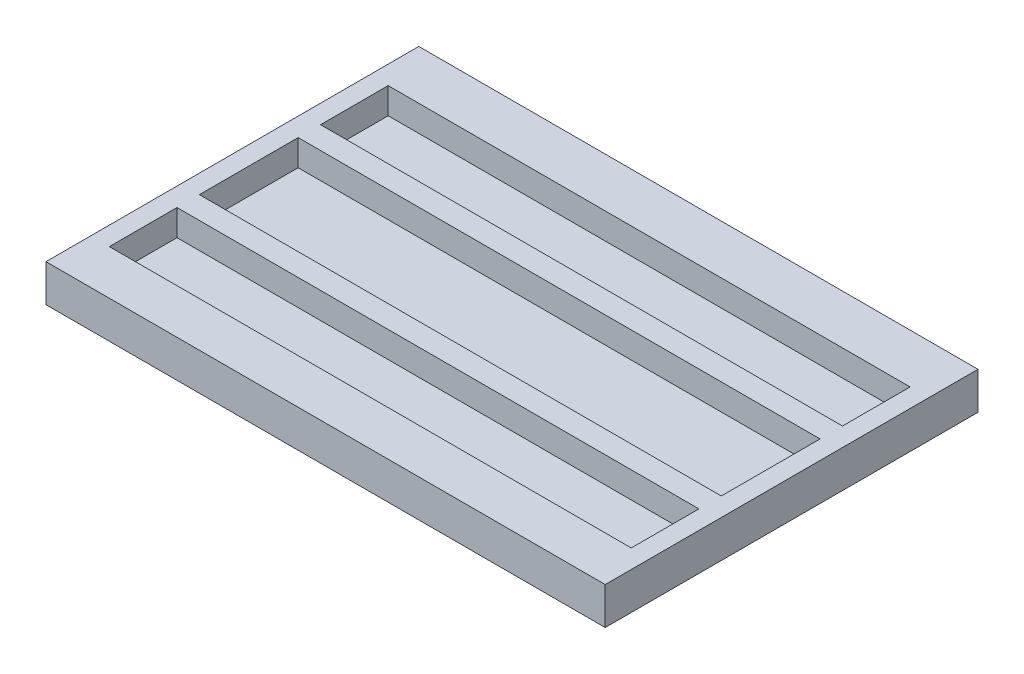
SolidWorks part; units mm, degrees
ref_plane "Front Plane" through (0, 0, 0) normal (0, 0, 1) x (1, 0, 0)
ref_plane "Top Plane" through (0, 0, 0) normal (0, 1, 0) x (1, 0, 0)
ref_plane "Right Plane" through (0, 0, 0) normal (1, 0, 0) x (0, 0, -1)
sketch "Sketch1" plane through (0, 0, 0) normal (0, 1, 0) x (1, 0, 0)
  line L1 (-75, 50) -> (75, 50)
  line L2 (-75, 50) -> (-75, -50)
  line L3 (-75, -50) -> (75, -50)
  line L4 (75, 50) -> (75, -50)
  line L5 (-75, 50) -> (75, -50) construction
  line L6 (-75, -50) -> (75, 50) construction
  point P0 (0, 0)
  dimension "D1" = 100
  dimension "D2" = 150
extrude "Boss-Extrude1" add sketch "Sketch1" along normal blind 10
sketch "Sketch2" plane through (0, 10, 0) normal (0, 1, 0) x (1, 0, 0)
  line L0 (-75, -0.6088) -> (75, -0.6088) construction
  line L1 (-75, 50) -> (-75, -50) construction
  line L2 (75, -50) -> (75, 50) construction
  line L3 (-75, 42.7905) -> (75, 42.7905) construction
  line L4 (-75, 36.7905) -> (75, 36.7905) construction
  line L5 (-75, 18.6405) -> (75, 18.6405) construction
  line L6 (-75, 12.6405) -> (75, 12.6405) construction
  line L7 (-75, -13.8581) -> (75, -13.8581) construction
  line L8 (-75, -19.8581) -> (75, -19.8581) construction
  line L9 (-75, -38.0081) -> (75, -38.0081) construction
  line L10 (-75, -44.0081) -> (75, -44.0081) construction
  line L11 (-70, -19.8581) -> (70, -19.8581)
  line L12 (-70, 36.7905) -> (70, 36.7905)
  line L13 (-70, 36.7905) -> (-70, 18.6405)
  line L14 (-70, 18.6405) -> (70, 18.6405)
  line L15 (70, 36.7905) -> (70, 18.6405)
  line L16 (70, -38.0081) -> (70, -19.8581)
  line L17 (-70, -38.0081) -> (70, -38.0081)
  line L18 (-70, -38.0081) -> (-70, -19.8581)
  line L19 (75, 50) -> (-75, 50) construction
  line L21 (-70, 12.6405) -> (70, 12.6405)
  line L22 (-70, 12.6405) -> (-70, -13.8581)
  line L23 (-70, -13.8581) -> (70, -13.8581)
  line L24 (70, 12.6405) -> (70, -13.8581)
  dimension "D4" = 5
  dimension "D5" = 5
  dimension "D6" = 140
  dimension "D7" = 19.2493
  dimension "D8" = 13.2095
  dimension "D9" = 5
  dimension "D1" = 6
  dimension "D2" = 18.15
  dimension "D3" = 6
extrude "Cut-Extrude1" cut sketch "Sketch2" against normal blind 7
